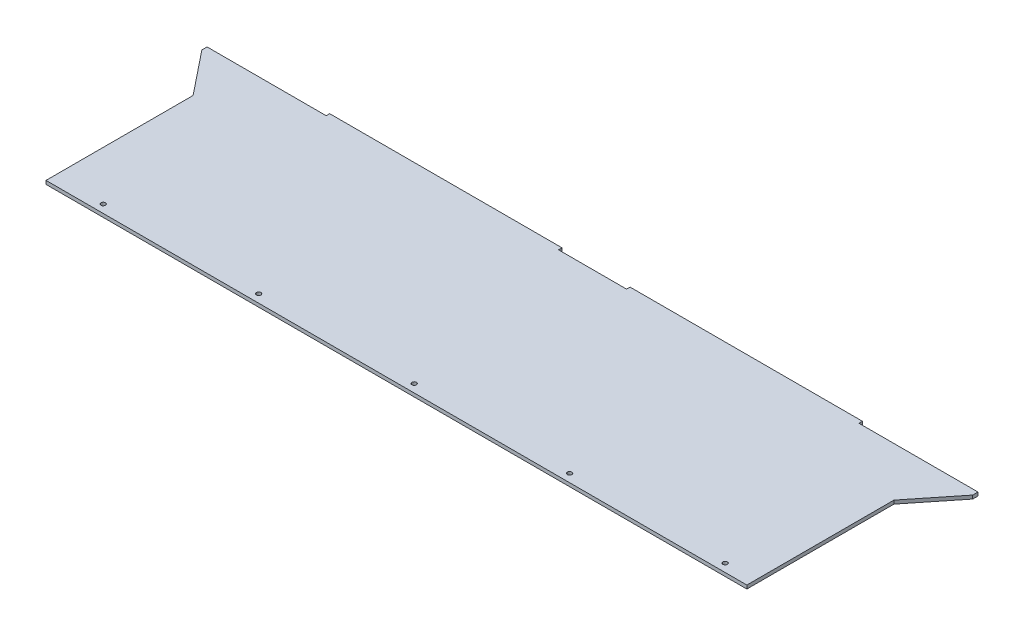
SolidWorks part; units mm, degrees
material "6061-T6 (SS)"
ref_plane "X-Y Datum" through (0, 0, 0) normal (0, 0, 1) x (1, 0, 0)
ref_plane "X-Z Datum" through (0, 0, 0) normal (0, 1, 0) x (1, 0, 0)
ref_plane "Y-Z Datum" through (0, 0, 0) normal (1, 0, 0) x (0, 0, -1)
sketch "Sketch1" plane through (0, 0, 0) normal (0, 1, 0) x (1, 0, 0)
  line L1 (-317.6778, 88.9) -> (317.6778, 88.9)
  line L2 (-317.6778, 88.9) -> (-317.6778, -88.9)
  line L3 (-317.6778, -88.9) -> (317.6778, -88.9)
  line L4 (317.6778, 88.9) -> (317.6778, -88.9)
  line L5 (-317.6778, 88.9) -> (317.6778, -88.9) construction
  line L6 (-317.6778, -88.9) -> (317.6778, 88.9) construction
  point P0 (0, 0)
  dimension "D1" = 635.3556
  dimension "D2" = 177.8
extrude "Boss-Extrude1" add sketch "Sketch1" along normal mid plane 3.175
sketch "Sketch2" plane through (0, 0, -88.9) normal (0, 0, -1) x (-1, 0, 0)
  line L0 (-241.4778, -1.5875) -> (-241.4778, 1.5875) construction
  line L1 (241.4778, -1.5875) -> (241.4778, 1.5875)
  line L2 (-241.4778, -1.5875) -> (-241.4778, 1.5875)
  line L3 (-241.4778, -1.5875) -> (-241.4778, 1.5875)
  line L4 (241.4778, -1.5875) -> (241.4778, 1.5875) construction
  line L5 (241.4778, -1.5875) -> (241.4778, 1.5875)
  line L20 (-317.6778, -1.5875) -> (317.6778, -1.5875) construction
  line L21 (-241.4778, -1.5875) -> (-30.8229, -1.5875)
  line L22 (30.8229, -1.5875) -> (241.4778, -1.5875)
  line L40 (30.8229, -1.5875) -> (30.8229, 1.5875)
  line L41 (30.8229, 1.5875) -> (241.4778, 1.5875)
  line L57 (-241.4778, 1.5875) -> (-30.8229, 1.5875)
  line L58 (-30.8229, 1.5875) -> (-30.8229, -1.5875)
  line M22 (-317.6778, -1.5875) -> (317.6778, -1.5875)
  line M24 (317.6778, 1.5875) -> (-317.6778, 1.5875)
extrude "Boss-Extrude2" add sketch "Sketch2" along normal blind 3.175 contours L58 L2 M24 M22 | L40 L1 M22 M24
sketch "Sketch3" plane through (0, 1.5875, 0) normal (0, 1, 0) x (1, 0, 0)
  line L0 (-317.6778, 88.9) -> (-349.4278, 88.9)
  line L1 (-349.4278, 88.9) -> (-349.4278, 84.1375)
  line L2 (-349.4278, 84.1375) -> (-317.6778, 44.45)
  line L3 (-317.6778, 88.9) -> (-317.6778, -88.9) construction
  line L16 (317.6778, -88.9) -> (317.6778, 88.9)
  line L17 (317.6778, 88.9) -> (241.4778, 88.9)
  line L18 (241.4778, 88.9) -> (241.4778, 92.075)
  line L19 (30.8229, 92.075) -> (30.8229, 88.9)
  line L20 (30.8229, 88.9) -> (-30.8229, 88.9)
  line L21 (-30.8229, 88.9) -> (-30.8229, 92.075)
  line L22 (-241.4778, 92.075) -> (-241.4778, 88.9)
  line L23 (-241.4778, 88.9) -> (-317.6778, 88.9)
  line L24 (241.4778, 92.075) -> (30.8229, 92.075)
  line L25 (241.4778, 92.075) -> (30.8229, 92.075)
  line L26 (-317.6778, 88.9) -> (-317.6778, -88.9)
  line L27 (-317.6778, -88.9) -> (317.6778, -88.9)
  line L38 (-317.6778, 88.9) -> (-317.6778, 44.45)
  line L40 (-30.8229, 92.075) -> (-241.4778, 92.075)
  line L41 (-30.8229, 92.075) -> (-241.4778, 92.075)
  line M26 (-317.6778, 88.9) -> (-317.6778, -88.9)
  dimension "D1" = 31.75
  dimension "D2" = 4.7625
  dimension "D3" = 44.45
  dimension "D4" = 0
extrude "Boss-Extrude3" add sketch "Sketch3" against normal blind 3.175 contours L1 L2 L0 M26
mirror "Mirror1" about plane through (0, 0, 0) normal (1, 0, 0) of "Boss-Extrude3"
sketch "Sketch4" plane through (0, 1.5875, 0) normal (0, 1, 0) x (1, 0, 0)
  line L0 (-273.2278, -88.9) -> (-273.2278, -81.534)
  line L1 (-317.6778, -88.9) -> (317.6778, -88.9) construction
  line L2 (-273.2278, -81.534) -> (-317.6778, -81.534)
  line L3 (-317.6778, 44.45) -> (-317.6778, -88.9) construction
  circle A0 centre (-273.2278, -81.534) radius 2.025
extrude "Cut-Extrude1" cut sketch "Sketch4" against normal blind 10 contours L0 A0 L2 | L2 A0 L0
pattern_linear "LPattern1" count 5 spacing 140.97 along (1, 0, 0) of "Cut-Extrude1"
